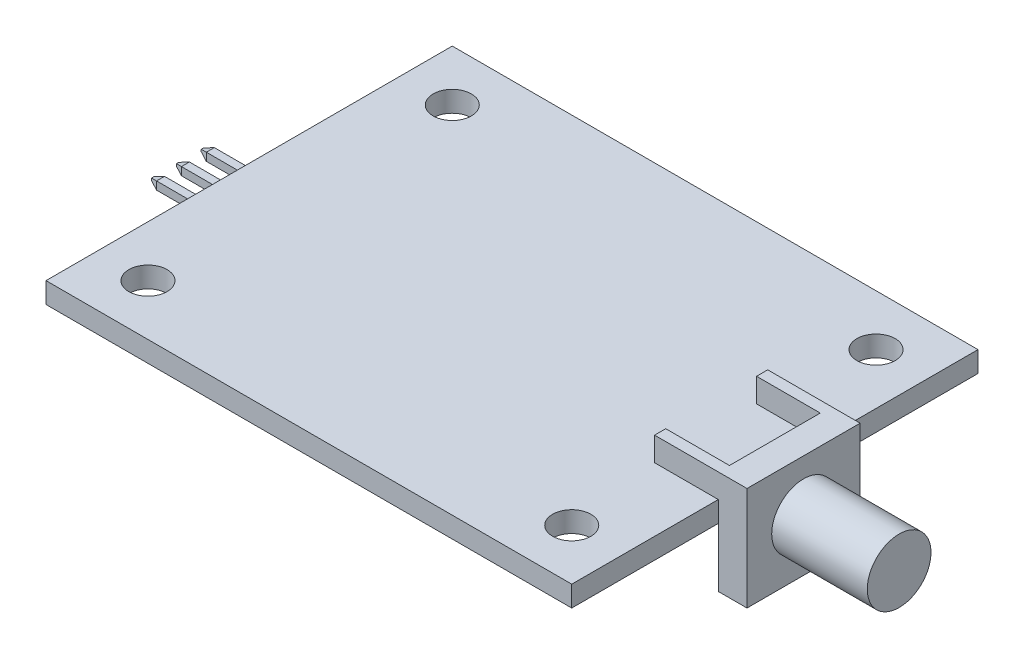
SolidWorks part; units mm, degrees
ref_plane "Front Plane" through (0, 0, 0) normal (0, 0, 1) x (1, 0, 0)
ref_plane "Top Plane" through (0, 0, 0) normal (0, 1, 0) x (1, 0, 0)
ref_plane "Right Plane" through (0, 0, 0) normal (1, 0, 0) x (0, 0, -1)
sketch "Sketch1" plane through (0, 0, 0) normal (0, 1, 0) x (1, 0, 0)
  line L1 (-20.955, -16.1925) -> (20.955, -16.1925)
  line L2 (-20.955, -16.1925) -> (-20.955, 16.1925)
  line L3 (-20.955, 16.1925) -> (20.955, 16.1925)
  line L4 (20.955, -16.1925) -> (20.955, 16.1925)
  line L5 (-20.955, -16.1925) -> (20.955, 16.1925) construction
  line L6 (-20.955, 16.1925) -> (20.955, -16.1925) construction
  point P0 (0, 0)
  dimension "D1" = 41.91
  dimension "D2" = 32.385
extrude "Boss-Extrude1" add sketch "Sketch1" along normal blind 1.651
sketch "Sketch2" plane through (0, 1.651, 0) normal (0, 1, 0) x (1, 0, 0)
  line L0 (20.955, 16.1925) -> (-20.955, 16.1925) construction
  line L1 (-20.955, 16.1925) -> (-20.955, -16.1925) construction
  line L2 (0, 0) -> (0, 16.1925) construction
  line L3 (0, 0) -> (20.955, 0) construction
  line L4 (20.955, -16.1925) -> (20.955, 16.1925) construction
  circle A0 centre (-16.891, 12.1285) radius 1.524
  circle A1 centre (16.891, 12.1285) radius 1.524
  circle A2 centre (-16.891, -12.1285) radius 1.524
  circle A3 centre (16.891, -12.1285) radius 1.524
  point P2 (-16.891, 13.6525)
  point P3 (-18.415, 12.1285)
  dimension "D1" = 3.048
  dimension "D2" = 2.54
  dimension "D3" = 2.54
extrude "Cut-Extrude1" cut sketch "Sketch2" against normal through all
sketch "Sketch3" plane through (0, 1.651, 0) normal (0, 1, 0) x (1, 0, 0)
  line L0 (20.955, -16.1925) -> (20.955, 16.1925) construction
  line L1 (15.875, -4.5085) -> (26.035, -4.5085) construction
  line L2 (15.875, -4.5085) -> (15.875, 4.5085) construction
  line L3 (15.875, 4.5085) -> (26.035, 4.5085) construction
  line L4 (26.035, -4.5085) -> (26.035, 4.5085) construction
  line L5 (15.875, -4.5085) -> (26.035, 4.5085) construction
  line L6 (15.875, 4.5085) -> (26.035, -4.5085) construction
  line L8 (15.875, 4.5085) -> (20.955, 4.5085)
  line L9 (15.875, 4.5085) -> (15.875, 3.6195)
  line L10 (15.875, 3.6195) -> (20.955, 3.6195)
  line L11 (20.955, 4.5085) -> (20.955, 3.6195)
  line L12 (15.875, -4.5085) -> (20.955, -4.5085)
  line L13 (15.875, -4.5085) -> (15.875, -3.6195)
  line L14 (15.875, -3.6195) -> (20.955, -3.6195)
  line L15 (20.955, -4.5085) -> (20.955, -3.6195)
  point P0 (20.955, 0)
  dimension "D1" = 5.08
  dimension "D2" = 9.017
  dimension "D3" = 0.889
extrude "Boss-Extrude2" add sketch "Sketch3" along normal blind 1.905
sketch "Sketch4" plane through (0, 1.651, 0) normal (0, 1, 0) x (1, 0, 0)
  line L0 (15.875, -4.5085) -> (20.955, -4.5085) construction
  line L1 (20.955, 4.5085) -> (23.241, 4.5085)
  line L2 (20.955, 4.5085) -> (20.955, -4.5085)
  line L3 (20.955, -4.5085) -> (23.241, -4.5085)
  line L4 (23.241, 4.5085) -> (23.241, -4.5085)
  line L5 (20.955, 4.5085) -> (15.875, 4.5085) construction
  line L6 (20.955, -16.1925) -> (20.955, -4.5085) construction
  dimension "D1" = 2.286
extrude "Boss-Extrude3" add sketch "Sketch4" along normal up to surface (1.905 mm away) and the other way blind 6.35 up to face at (18.415, 3.556, -4.064)
sketch "Sketch5" plane through (23.241, 0, 0) normal (1, 0, 0) x (0, 0, -1)
  line L0 (-4.5085, -4.699) -> (4.5085, 3.556) construction
  circle A0 centre (0, -0.5715) radius 2.54
  point P6 (0, 0)
  dimension "D1" = 5.08
extrude "Boss-Extrude4" add sketch "Sketch5" along normal blind 7.62
sketch "Sketch6" plane through (0, 0, 0) normal (0, -1, 0) x (1, 0, 0)
  line L0 (20.955, 0) -> (-20.955, 0) construction
  line L1 (20.955, 4.5085) -> (20.955, -4.5085) construction
  line L2 (-20.955, -16.1925) -> (-20.955, 16.1925) construction
  line L4 (-18.415, -3.9688) -> (-15.875, -3.9688)
  line L5 (-18.415, -3.9688) -> (-18.415, 3.9687)
  line L6 (-18.415, 3.9687) -> (-15.875, 3.9687)
  line L7 (-15.875, -3.9688) -> (-15.875, 3.9687)
  line L8 (-18.415, -3.9688) -> (-15.875, 3.9687) construction
  line L9 (-18.415, 3.9687) -> (-15.875, -3.9688) construction
  point P6 (-17.145, 0)
  dimension "D1" = 7.9375
  dimension "D2" = 2.54
  dimension "D3" = 2.54
extrude "Boss-Extrude5" add sketch "Sketch6" along normal blind 2.54
sketch "Sketch7" plane through (-18.415, 0, 0) normal (-1, 0, 0) x (0, 0, 1)
  line L0 (3.9687, -1.27) -> (1.9844, -1.27) construction
  line L1 (3.9687, -2.54) -> (3.9687, 0) construction
  line L2 (1.9844, -1.27) -> (0, -1.27) construction
  line L3 (0, -1.27) -> (-1.9844, -1.27) construction
  line L4 (-1.9844, -1.27) -> (-3.9688, -1.27) construction
  line L5 (-3.9688, -2.54) -> (-3.9688, 0) construction
  line L7 (2.3019, -0.9525) -> (1.6669, -0.9525)
  line L8 (2.3019, -0.9525) -> (2.3019, -1.5875)
  line L9 (2.3019, -1.5875) -> (1.6669, -1.5875)
  line L10 (1.6669, -0.9525) -> (1.6669, -1.5875)
  line L11 (2.3019, -0.9525) -> (1.6669, -1.5875) construction
  line L12 (2.3019, -1.5875) -> (1.6669, -0.9525) construction
  line L13 (0.3175, -0.9525) -> (-0.3175, -0.9525)
  line L14 (0.3175, -0.9525) -> (0.3175, -1.5875)
  line L15 (0.3175, -1.5875) -> (-0.3175, -1.5875)
  line L16 (-0.3175, -0.9525) -> (-0.3175, -1.5875)
  line L17 (0.3175, -0.9525) -> (-0.3175, -1.5875) construction
  line L18 (0.3175, -1.5875) -> (-0.3175, -0.9525) construction
  line L19 (-1.6669, -0.9525) -> (-2.3019, -0.9525)
  line L20 (-1.6669, -0.9525) -> (-1.6669, -1.5875)
  line L21 (-1.6669, -1.5875) -> (-2.3019, -1.5875)
  line L22 (-2.3019, -0.9525) -> (-2.3019, -1.5875)
  line L23 (-1.6669, -0.9525) -> (-2.3019, -1.5875) construction
  line L24 (-1.6669, -1.5875) -> (-2.3019, -0.9525) construction
  dimension "D1" = 0.635
extrude "Boss-Extrude6" add sketch "Sketch7" along normal blind 7.62
sketch "Sketch8" plane through (-26.035, 0, 0) normal (-1, 0, 0) x (0, 0, 1)
  line L0 (-2.3019, -0.9525) -> (-2.3019, -1.5875) construction
  line L1 (-2.3019, -1.5875) -> (-1.6669, -1.5875) construction
  line L2 (-1.6669, -1.5875) -> (-1.6669, -0.9525) construction
  line L3 (-1.6669, -0.9525) -> (-2.3019, -0.9525) construction
  line L4 (-0.3175, -0.9525) -> (-0.3175, -1.5875) construction
  line L5 (-0.3175, -1.5875) -> (0.3175, -1.5875) construction
  line L6 (0.3175, -1.5875) -> (0.3175, -0.9525) construction
  line L7 (0.3175, -0.9525) -> (-0.3175, -0.9525) construction
  line L8 (1.6669, -0.9525) -> (1.6669, -1.5875) construction
  line L9 (1.6669, -1.5875) -> (2.3019, -1.5875) construction
  line L10 (2.3019, -1.5875) -> (2.3019, -0.9525) construction
  line L11 (2.3019, -0.9525) -> (1.6669, -0.9525) construction
  line L12 (-2.3019, -0.9525) -> (-2.3019, -1.5875)
  line L13 (-2.3019, -1.5875) -> (-1.6669, -1.5875)
  line L14 (-1.6669, -1.5875) -> (-1.6669, -0.9525)
  line L15 (-1.6669, -0.9525) -> (-2.3019, -0.9525)
  line L16 (-0.3175, -0.9525) -> (-0.3175, -1.5875)
  line L17 (-0.3175, -1.5875) -> (0.3175, -1.5875)
  line L18 (0.3175, -1.5875) -> (0.3175, -0.9525)
  line L19 (0.3175, -0.9525) -> (-0.3175, -0.9525)
  line L20 (1.6669, -0.9525) -> (1.6669, -1.5875)
  line L21 (1.6669, -1.5875) -> (2.3019, -1.5875)
  line L22 (2.3019, -1.5875) -> (2.3019, -0.9525)
  line L23 (2.3019, -0.9525) -> (1.6669, -0.9525)
extrude "Boss-Extrude7" add sketch "Sketch8" along normal blind 0.635 draft 20
